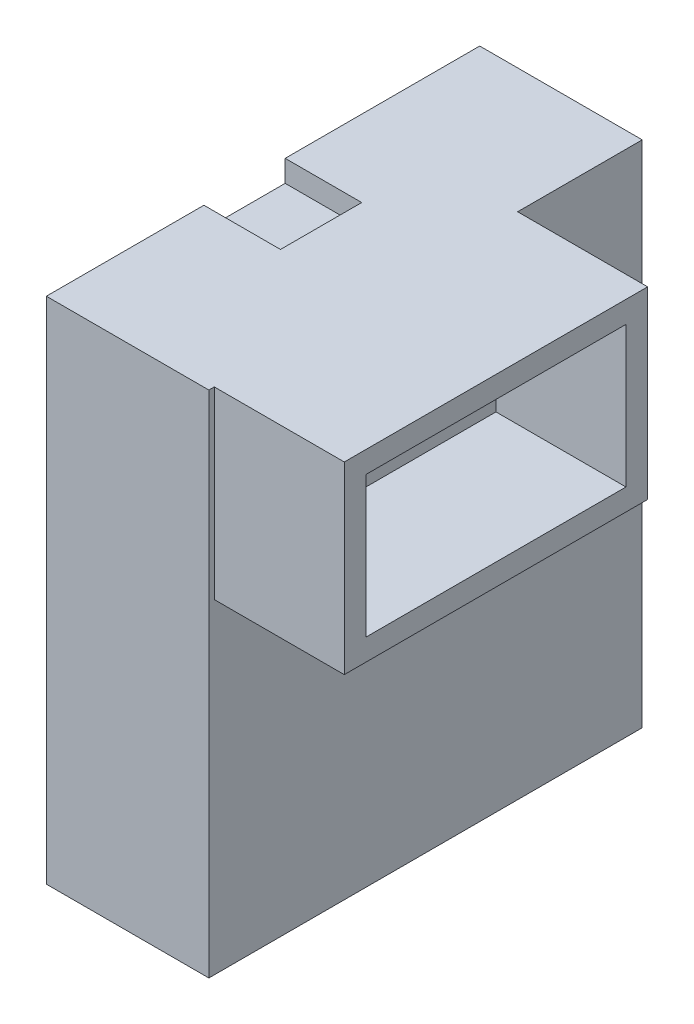
SolidWorks part; units mm, degrees
ref_plane "Front Plane" through (0, 0, 0) normal (0, 0, 1) x (1, 0, 0)
ref_plane "Top Plane" through (0, 0, 0) normal (0, 1, 0) x (1, 0, 0)
ref_plane "Right Plane" through (0, 0, 0) normal (1, 0, 0) x (0, 0, -1)
sketch "Sketch1" plane through (0, 0, 0) normal (1, 0, 0) x (0, 0, -1)
  line L1 (-20, -23.5) -> (20, -23.5)
  line L2 (-20, -23.5) -> (-20, 23.5)
  line L3 (-20, 23.5) -> (20, 23.5)
  line L4 (20, -23.5) -> (20, 23.5)
  line L5 (-20, -23.5) -> (20, 23.5) construction
  line L6 (-20, 23.5) -> (20, -23.5) construction
  point P0 (0, 0)
  dimension "D1" = 40
  dimension "D2" = 47
extrude "Boss-Extrude1" add sketch "Sketch1" along normal blind 15
sketch "Sketch2" plane through (15, 0, 0) normal (1, 0, 0) x (0, 0, -1)
  line L0 (-20, 23.5) -> (-20, -23.5) construction
  line L1 (-17.5, 21.5) -> (6.5, 21.5)
  line L2 (-17.5, 21.5) -> (-17.5, 8.5)
  line L3 (-17.5, 8.5) -> (6.5, 8.5)
  line L4 (6.5, 21.5) -> (6.5, 8.5)
  line L5 (-17.5, 21.5) -> (6.5, 8.5) construction
  line L6 (-17.5, 8.5) -> (6.5, 21.5) construction
  line L7 (20, 23.5) -> (-20, 23.5) construction
  line L8 (-19.5, 23.5) -> (8.5, 23.5)
  line L9 (8.5, 23.5) -> (8.5, 6.5)
  line L10 (-19.5, 6.5) -> (8.5, 6.5)
  line L11 (-19.5, 23.5) -> (-19.5, 6.5)
  point P0 (33.6303, 36.1956)
  dimension "D1" = 24
  dimension "D2" = 13
  dimension "D3" = 2.5
  dimension "D4" = 2
  dimension "D5" = 2
extrude "Boss-Extrude2" add sketch "Sketch2" along normal blind 12
sketch "Sketch4" plane through (0, 23.5, 0) normal (0, 1, 0) x (1, 0, 0)
  line L0 (0, 20) -> (0, -20) construction
  line L1 (0, -5.4577) -> (7.0674, -5.4577)
  line L2 (0, -5.4577) -> (0, 2.0423)
  line L3 (0, 2.0423) -> (7.0674, 2.0423)
  line L4 (7.0674, -5.4577) -> (7.0674, 2.0423)
  dimension "D1" = 7.5
extrude "Cut-Extrude1" cut sketch "Sketch4" against normal blind 2
